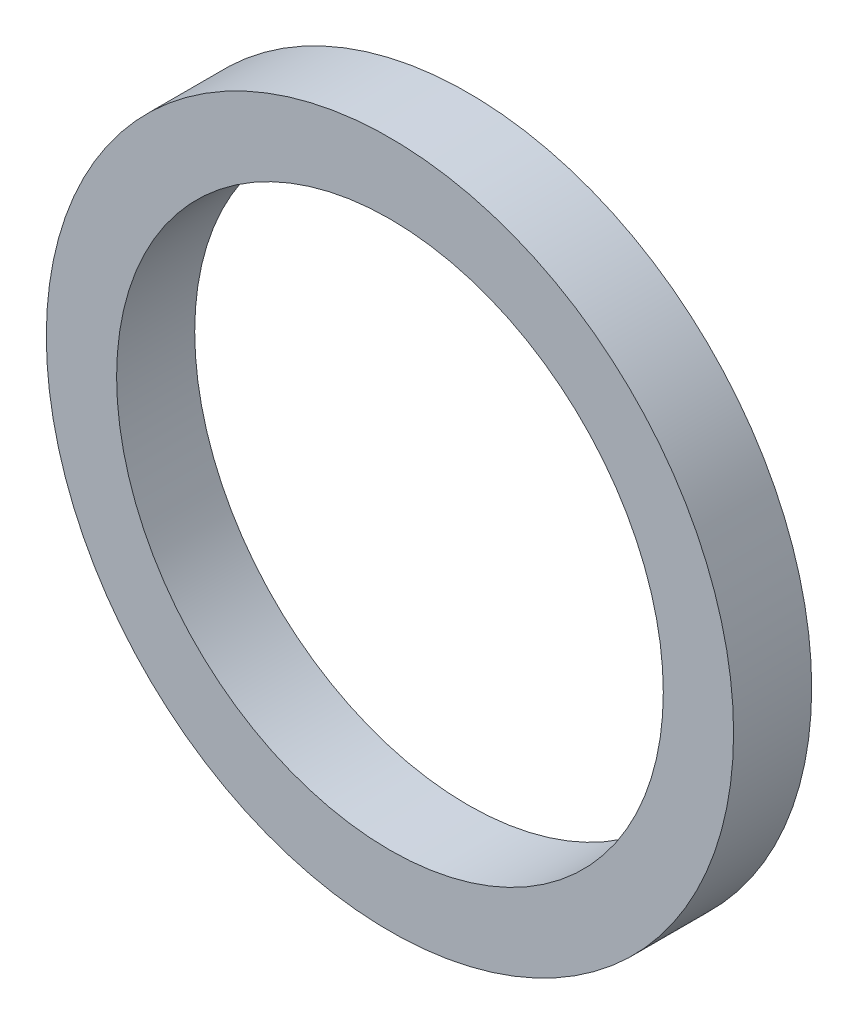
SolidWorks part; units mm, degrees
ref_plane "前视基准面" through (0, 0, 0) normal (0, 0, 1) x (1, 0, 0)
ref_plane "上视基准面" through (0, 0, 0) normal (0, 1, 0) x (1, 0, 0)
ref_plane "右视基准面" through (0, 0, 0) normal (1, 0, 0) x (0, 0, -1)
other "Configuration Table"
sketch "草图1" plane through (0, 0, 0) normal (0, 0, 1) x (1, 0, 0)
  circle A0 centre (0, 0) radius 17.5
  circle A1 centre (0, 0) radius 22
  dimension "D1" = 35
  dimension "D2" = 44
extrude "凸台-拉伸1" add sketch "草图1" along normal blind 5
